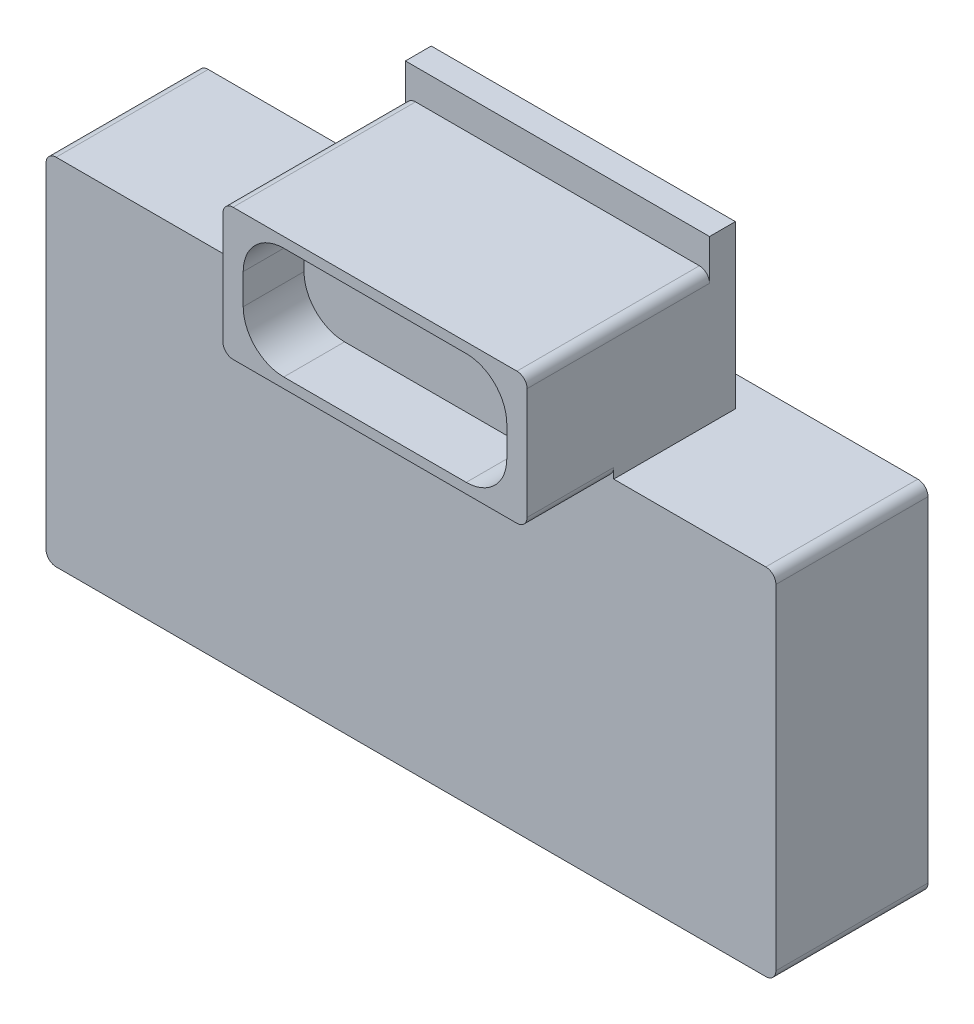
SolidWorks part; units mm, degrees
ref_plane "正面" through (0, 0, 0) normal (0, 0, 1) x (1, 0, 0)
ref_plane "平面" through (0, 0, 0) normal (0, 1, 0) x (1, 0, 0)
ref_plane "右側面" through (0, 0, 0) normal (1, 0, 0) x (0, 0, -1)
sketch "ｽｹｯﾁ1" plane through (0, 0, 0) normal (0, 0, 1) x (1, 0, 0)
  line L1 (0, 0) -> (72, 0)
  line L2 (0, 0) -> (0, 35)
  line L3 (0, 35) -> (72, 35)
  line L4 (72, 0) -> (72, 35)
  dimension "D1" = 35
  dimension "D2" = 72
extrude "ﾎﾞｽ - 押し出し1" add sketch "ｽｹｯﾁ1" along normal blind 15
sketch "ｽｹｯﾁ2" plane through (0, 35, 0) normal (0, 1, 0) x (1, 0, 0)
  line L0 (72, 0) -> (0, 0) construction
  line L1 (26, -3) -> (56, -3)
  line L2 (26, -3) -> (26, -5.549)
  line L3 (26, -5.549) -> (56, -5.549)
  line L4 (56, -3) -> (56, -5.549)
  line L5 (72, -15) -> (72, 0) construction
  dimension "D1" = 3
  dimension "D2" = 30
  dimension "D3" = 16
extrude "ﾎﾞｽ - 押し出し2" add sketch "ｽｹｯﾁ2" along normal blind 16
sketch "ｽｹｯﾁ3" plane through (0, 0, 5.549) normal (0, 0, 1) x (1, 0, 0)
  line L0 (56, 51) -> (56, 35) construction
  line L1 (26, 35) -> (56, 35)
  line L2 (26, 35) -> (26, 48)
  line L3 (26, 48) -> (56, 48)
  line L4 (56, 35) -> (56, 48)
  dimension "D1" = 13
extrude "ﾎﾞｽ - 押し出し3" add sketch "ｽｹｯﾁ3" along normal blind 18
sketch "ｽｹｯﾁ4" plane through (0, 0, 23.549) normal (0, 0, 1) x (1, 0, 0)
  line L0 (26, 35) -> (56, 35) construction
  line L1 (28, 36) -> (54, 36)
  line L2 (28, 36) -> (28, 47)
  line L3 (28, 47) -> (54, 47)
  line L4 (54, 36) -> (54, 47)
  line L5 (26, 48) -> (26, 35) construction
  line L6 (56, 35) -> (56, 48) construction
  line L7 (56, 48) -> (26, 48) construction
  dimension "D1" = 1
  dimension "D2" = 2
  dimension "D3" = 2
  dimension "D4" = 1
extrude "ｶｯﾄ - 押し出し1" cut sketch "ｽｹｯﾁ4" against normal blind 6
fillet "ﾌｨﾚｯﾄ1" radius 4 4 edges at (54, 36, 20.549) (54, 47, 20.549) (28, 36, 20.549) (28, 47, 20.549)
fillet "ﾌｨﾚｯﾄ3" radius 4 1 edges at (26, 35, 9)
fillet "ﾌｨﾚｯﾄ2" radius 1 8 edges at (0, 35, 7.5) (0, 0, 7.5) (72, 0, 7.5) (72, 35, 7.5) (56, 35, 19.2745) (26, 35, 19.2745) (56, 48, 14.549) (26, 48, 14.549)
